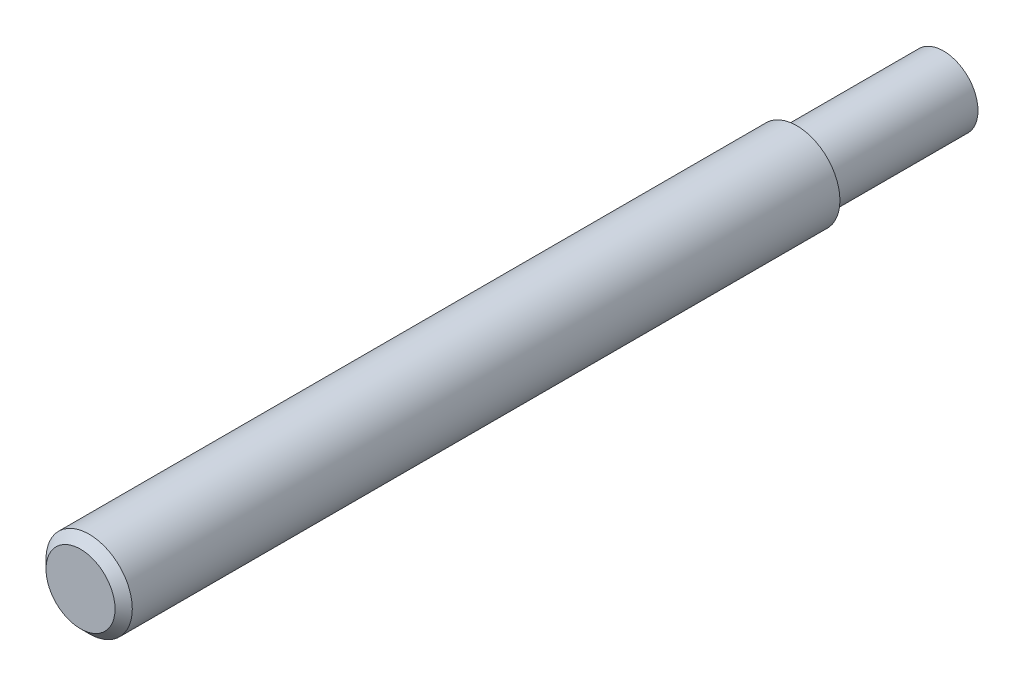
SolidWorks part; units mm, degrees
material "1.7225 (42CrMo4)"
ref_plane "Front Plane" through (0, 0, 0) normal (0, 0, 1) x (1, 0, 0)
ref_plane "Top Plane" through (0, 0, 0) normal (0, 1, 0) x (1, 0, 0)
ref_plane "Right Plane" through (0, 0, 0) normal (1, 0, 0) x (0, 0, -1)
sketch "Esquisse1" plane through (0, 0, 0) normal (0, 0, 1) x (1, 0, 0)
  circle A0 centre (0, 0) radius 4
  dimension "D1" = 8
extrude "Boss.-Extru.1" add sketch "Esquisse1" along normal blind 17
sketch "Esquisse2" plane through (0, 0, 17) normal (0, 0, 1) x (1, 0, 0)
  circle A0 centre (0, 0) radius 5
  dimension "D1" = 10
extrude "Boss.-Extru.2" add sketch "Esquisse2" along normal blind 83
chamfer "Chanfrein1" distance 1 angle 45 1 edges at (5, 0, 100)
hole_wizard "Trou taraudé M61" positions "Esquisse3" profile "Esquisse4" tap size "M6" standard "ISO"
sketch "Esquisse3" plane through (0, 0, 0) normal (0, 0, -1) x (-1, 0, 0)
  point P0 (0, 0)
sketch "Esquisse4" plane through (0, 0, 0) normal (1, 0, 0) x (0, 1, 0)
  line L0 (0, 0) -> (0, 16.5022)
  line L1 (0, 16.5022) -> (2.5, 15)
  line L2 (2.5, 15) -> (2.5, 0.5774)
  line L3 (2.5, 0.5774) -> (3.5, 0)
  line L5 (3.5, 0) -> (0, 0)
  line L6 (-2.5, 0.5774) -> (-3.5, 0) construction
  line L10 (0, 16.5022) -> (-2.5, 15) construction
  line L11 (0, -6.35) -> (0, 107.95) construction
  dimension "Diamètre du trou pour taraudage" = 5
  dimension "Profondeur du trou pour taraudage" = 15
  dimension "Diamètre du fraisage entrant" = 7
  dimension "Angle du fraisage entrant" = 120
  dimension "Angle de pointe" = 118
cosmetic thread "Filetage de perçage1"
